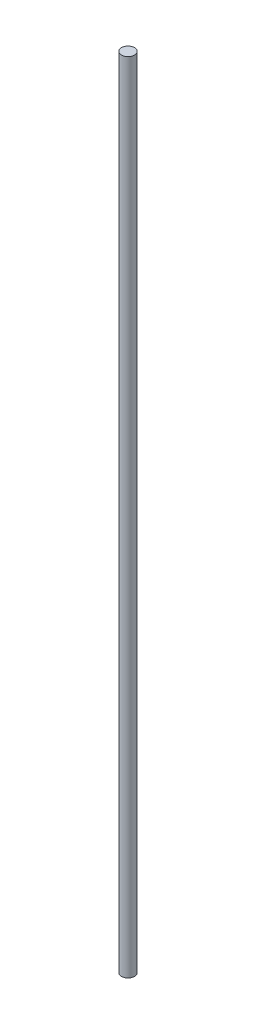
SolidWorks part; units mm, degrees
ref_plane "Front Plane" through (0, 0, 0) normal (0, 0, 1) x (1, 0, 0)
ref_plane "Top Plane" through (0, 0, 0) normal (0, 1, 0) x (1, 0, 0)
ref_plane "Right Plane" through (0, 0, 0) normal (1, 0, 0) x (0, 0, -1)
sketch "Sketch1" plane through (0, 0, 0) normal (0, 1, 0) x (1, 0, 0)
  circle A0 centre (0, 0) radius 4
  dimension "D1" = 8
extrude "Boss-Extrude1" add sketch "Sketch1" along normal blind 490.56
equation "\"d\"= 8"
equation "\"l\"= 483.2 + 6.36 + 1"
equation "\"D1@Boss-Extrude1\"=\"l\""
equation "\"D1@Sketch1\"=\"d\""
